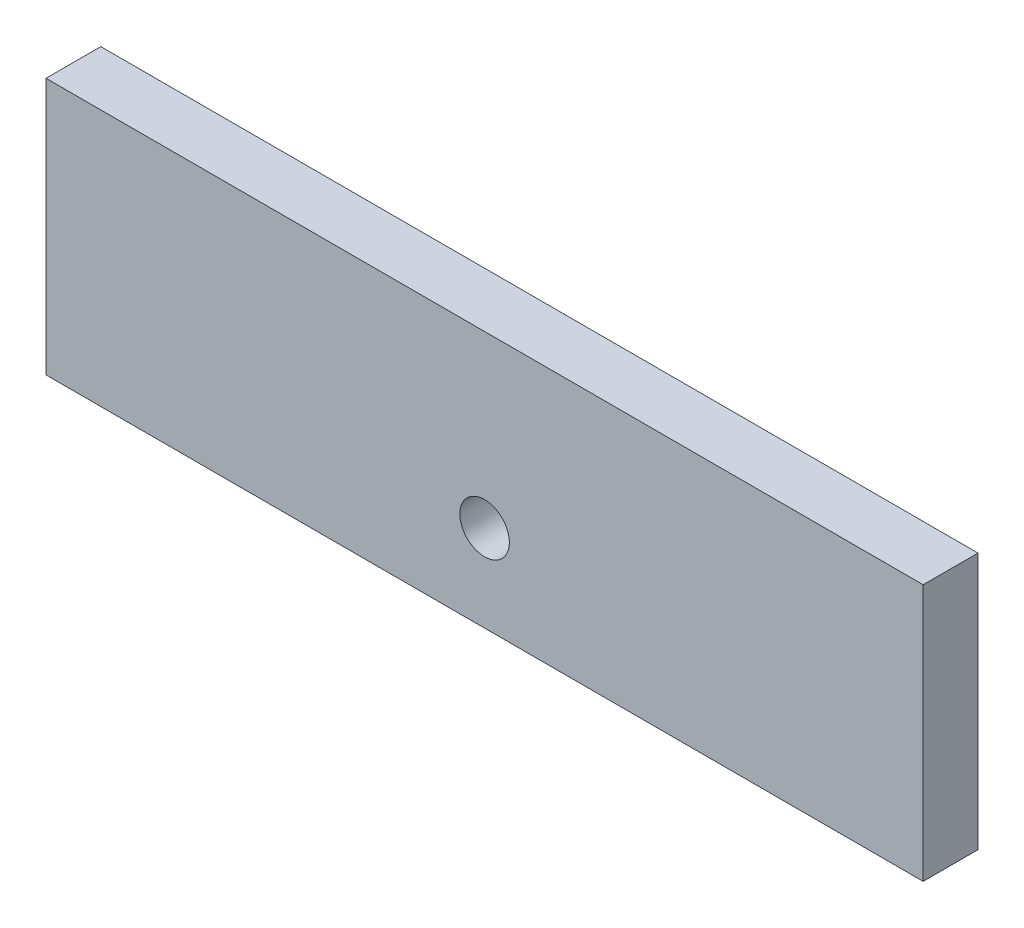
SolidWorks part; units mm, degrees
ref_plane "Front Plane" through (0, 0, 0) normal (0, 0, 1) x (1, 0, 0)
ref_plane "Top Plane" through (0, 0, 0) normal (0, 1, 0) x (1, 0, 0)
ref_plane "Right Plane" through (0, 0, 0) normal (1, 0, 0) x (0, 0, -1)
sketch "Sketch1" plane through (0, 0, 0) normal (0, 0, 1) x (1, 0, 0)
  line L1 (0, 0) -> (101.6, 0)
  line L2 (0, 0) -> (0, 29.7561)
  line L3 (0, 29.7561) -> (101.6, 29.7561)
  line L4 (101.6, 0) -> (101.6, 29.7561)
  dimension "D1" = 29.7561
  dimension "D2" = 101.6
extrude "Boss-Extrude1" add sketch "Sketch1" against normal blind 6.35
sketch "Sketch2" plane through (0, 0, 0) normal (0, 0, 1) x (1, 0, 0)
  line L0 (50.8, 29.7561) -> (50.8, 10.0266) construction
  line L1 (101.6, 29.7561) -> (0, 29.7561) construction
  circle A0 centre (50.8, 10.0266) radius 2.8702
  dimension "D1" = 5.7404
  dimension "D2" = 19.7294
extrude "Cut-Extrude1" cut sketch "Sketch2" against normal through all
